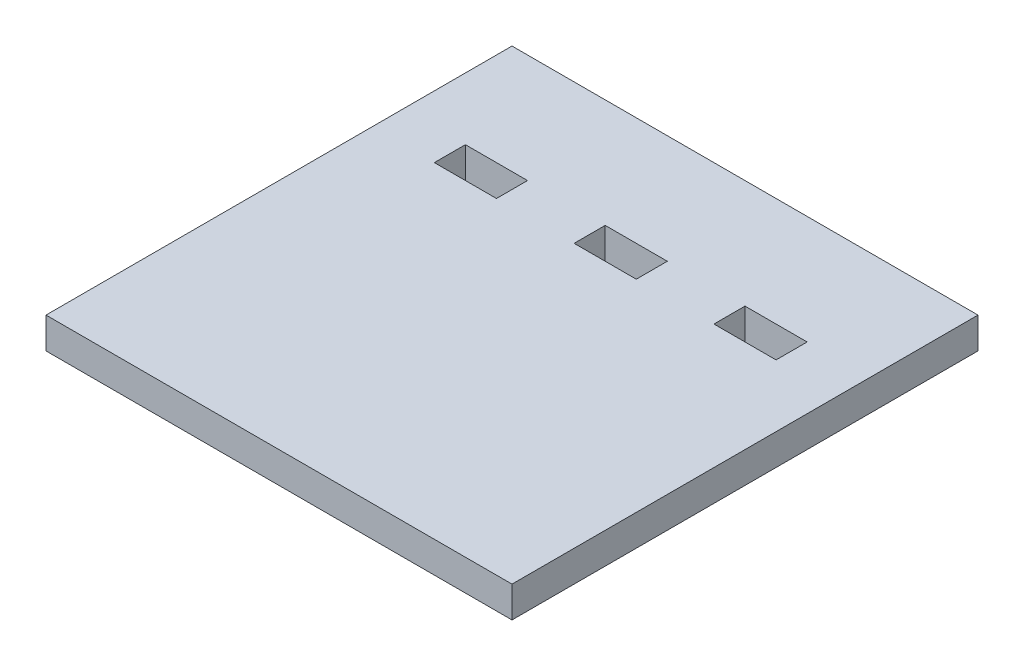
SolidWorks part; units mm, degrees
material "ABS PC"
ref_plane "Front Plane" through (0, 0, 0) normal (0, 0, 1) x (1, 0, 0)
ref_plane "Top Plane" through (0, 0, 0) normal (0, 1, 0) x (1, 0, 0)
ref_plane "Right Plane" through (0, 0, 0) normal (1, 0, 0) x (0, 0, -1)
sketch "Sketch1" plane through (0, 0, 0) normal (0, 1, 0) x (1, 0, 0)
  line L0 (-75, 35) -> (75, 35) construction
  line L1 (-75, -75) -> (75, -75)
  line L2 (-75, -75) -> (-75, 75)
  line L3 (-75, 75) -> (75, 75)
  line L4 (75, -75) -> (75, 75)
  line L5 (-75, -75) -> (75, 75) construction
  line L6 (-75, 75) -> (75, -75) construction
  line L7 (0, 35) -> (0, 0) construction
  line L8 (-55, 30) -> (-35, 30)
  line L9 (-55, 30) -> (-55, 40)
  line L10 (-55, 40) -> (-35, 40)
  line L11 (-35, 30) -> (-35, 40)
  line L12 (-55, 30) -> (-35, 40) construction
  line L13 (-55, 40) -> (-35, 30) construction
  line L14 (-10, 30) -> (10, 30)
  line L15 (-10, 30) -> (-10, 40)
  line L16 (-10, 40) -> (10, 40)
  line L17 (10, 30) -> (10, 40)
  line L18 (-10, 30) -> (10, 40) construction
  line L19 (-10, 40) -> (10, 30) construction
  line L20 (35, 30) -> (35, 40)
  line L21 (55, 40) -> (35, 40)
  line L22 (55, 30) -> (55, 40)
  line L23 (55, 30) -> (35, 30)
  point P0 (0, 0)
  point P8 (-45, 35)
  point P13 (0, 35)
  dimension "D1" = 150
  dimension "D2" = 150
  dimension "D3" = 40
  dimension "D4" = 20
  dimension "D5" = 10
  dimension "D6" = 20
  dimension "D7" = 20
  dimension "D8" = 10
extrude "Boss-Extrude1" add sketch "Sketch1" along normal blind 10
